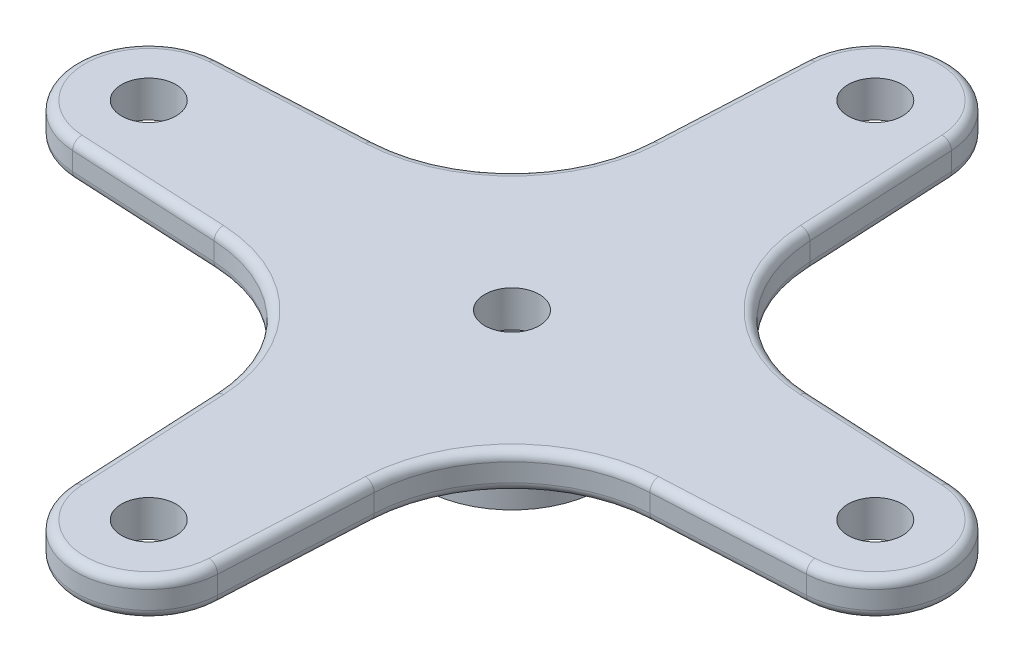
SolidWorks part; units mm, degrees
material "cardboard"
ref_plane "Front Plane" through (0, 0, 0) normal (0, 0, 1) x (1, 0, 0)
ref_plane "Top Plane" through (0, 0, 0) normal (0, 1, 0) x (1, 0, 0)
ref_plane "Right Plane" through (0, 0, 0) normal (1, 0, 0) x (0, 0, -1)
sketch "Sketch1" plane through (0, 0, 0) normal (0, 1, 0) x (1, 0, 0)
  circle A0 centre (0, 0) radius 3
  circle A1 centre (0, 0) radius 5
  dimension "D1" = 6
  dimension "D2" = 10
extrude "Boss-Extrude1" add sketch "Sketch1" along normal blind 4
sketch "Sketch5" plane through (0, 4, 0) normal (0, 1, 0) x (1, 0, 0)
  line L0 (0, 0) -> (0, 20) construction
  line L1 (-3.995, 20.2) -> (-4.4057, 11.9957)
  line L2 (3.995, 20.2) -> (4.4057, 11.9957)
  line L3 (20.2, 3.995) -> (11.9957, 4.4057)
  line L4 (20.2, -3.995) -> (11.9957, -4.4057)
  line L5 (3.995, -20.2) -> (4.4057, -11.9957)
  line L6 (-3.995, -20.2) -> (-4.4057, -11.9957)
  line L7 (-20.2, -3.995) -> (-11.9957, -4.4057)
  line L8 (-20.2, 3.995) -> (-11.9957, 4.4057)
  arc A0 (3.995, 20.2) -> (-3.995, 20.2) centre (0, 20) ccw
  arc A2 (20.2, -3.995) -> (20.2, 3.995) centre (20, 0) ccw
  arc A3 (-3.995, -20.2) -> (3.995, -20.2) centre (0, -20) ccw
  arc A4 (-20.2, 3.995) -> (-20.2, -3.995) centre (-20, 0) ccw
  arc A5 (-11.9957, -4.4057) -> (-4.4057, -11.9957) centre (-12.3957, -12.3957) cw
  arc A6 (4.4057, -11.9957) -> (11.9957, -4.4057) centre (12.3957, -12.3957) cw
  arc A7 (11.9957, 4.4057) -> (4.4057, 11.9957) centre (12.3957, 12.3957) cw
  arc A8 (-4.4057, 11.9957) -> (-11.9957, 4.4057) centre (-12.3957, 12.3957) cw
  circle A9 centre (0, 20) radius 1.5
  circle A10 centre (20, 0) radius 1.5
  circle A11 centre (0, -20) radius 1.5
  circle A12 centre (-20, 0) radius 1.5
  point P30 (0, 0)
  point P37 (0, 0)
  dimension "D2" = 8
  dimension "D3" = 8
  dimension "D5" = 3
  dimension "D1" = 20
  dimension "D4" = 4
  dimension "D6" = 4
extrude "Boss-Extrude3" add sketch "Sketch5" along normal blind 2
sketch "Sketch6" plane through (0, 6, 0) normal (0, 1, 0) x (1, 0, 0)
  circle A0 centre (0, 0) radius 1.5
  dimension "D1" = 3
extrude "Cut-Extrude1" cut sketch "Sketch6" against normal through all
fillet "Fillet1" radius 0.5 32 edges at (-4.2004, 4, 16.0979) (-6.7389, 4, 6.7389) (-16.0979, 4, 4.2004) (-24, 4, 0) (-16.0979, 4, -4.2004) (-6.7389, 4, -6.7389) (-4.2004, 4, -16.0979) (0, 4, -24) (4.2004, 4, -16.0979) (6.7389, 4, -6.7389) (16.0979, 4, -4.2004) (24, 4, 0) (16.0979, 4, 4.2004) (6.7389, 4, 6.7389) (4.2004, 4, 16.0979) (0, 6, 24) (-4.2004, 6, 16.0979) (-6.7389, 6, 6.7389) (-16.0979, 6, 4.2004) (-24, 6, 0) (-16.0979, 6, -4.2004) (-6.7389, 6, -6.7389) (-4.2004, 6, -16.0979) (0, 6, -24) (4.2004, 6, -16.0979) (6.7389, 6, -6.7389) (16.0979, 6, -4.2004) (24, 6, 0) (16.0979, 6, 4.2004) (6.7389, 6, 6.7389) (0, 4, 24) (4.2004, 6, 16.0979)
fillet "Fillet2" radius 0.5 1 edges at (0, 4, 5)
